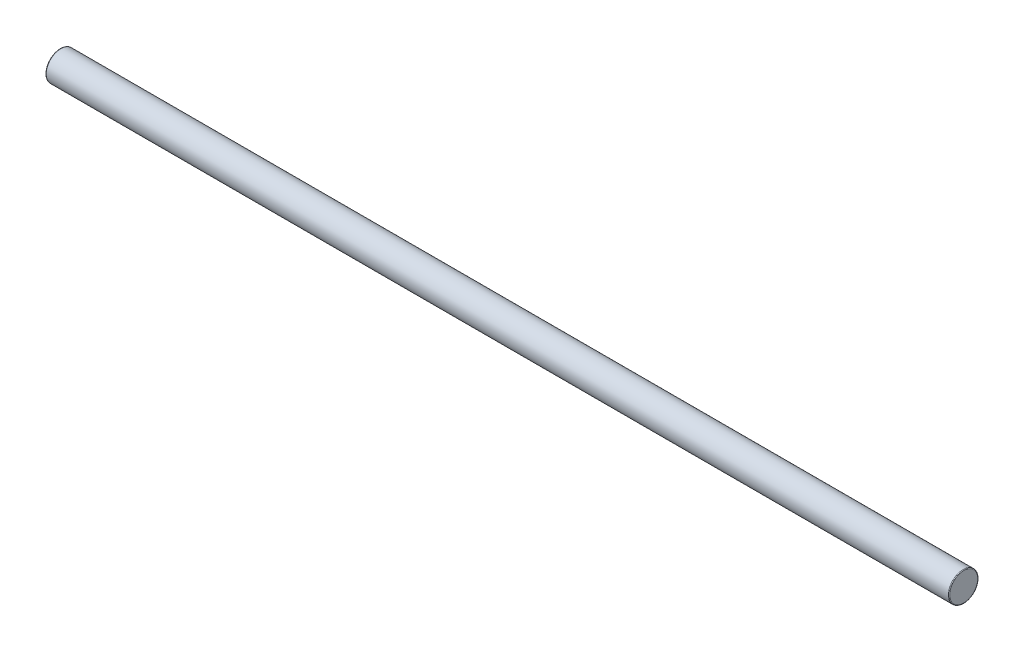
SolidWorks part; units mm, degrees
ref_plane "Front Plane" through (0, 0, 0) normal (1, 0, 0) x (0, 1, 0)
ref_plane "Top Plane" through (0, 0, 0) normal (0, 0, 1) x (0, 1, 0)
ref_plane "Right Plane" through (0, 0, 0) normal (0, 1, 0) x (-1, 0, 0)
sketch "Sketch1" plane through (0, 0, 0) normal (1, 0, 0) x (0, 1, 0)
  circle A0 centre (976.376, 0) radius 31.731
extrude "Boss-Extrude1" add sketch "Sketch1" along normal blind 1952.752
sketch "Sketch3" plane through (0, 0, 0) normal (0, 1, 0) x (-1, 0, 0)
  circle A0 centre (976.376, 0) radius 22.0218
fillet "Fillet1" radius 1.524 2 edges at (1952.752, 976.376, -31.731) (0, 976.376, -31.731)
